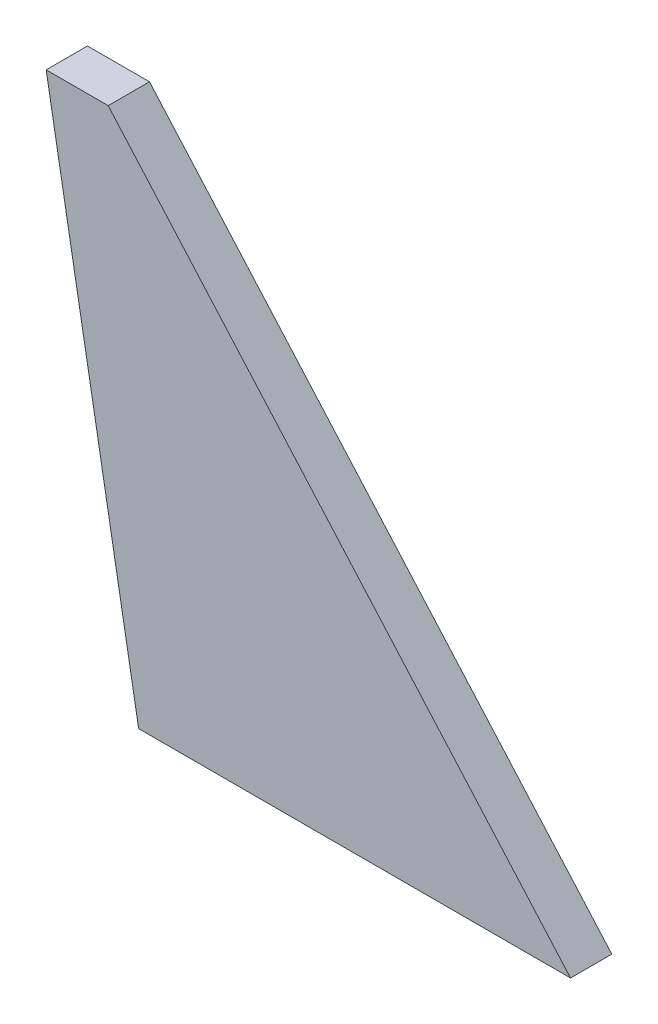
SolidWorks part; units mm, degrees
ref_plane "Front Plane" through (0, 0, 0) normal (0, 0, 1) x (1, 0, 0)
ref_plane "Top Plane" through (0, 0, 0) normal (0, 1, 0) x (1, 0, 0)
ref_plane "Right Plane" through (0, 0, 0) normal (1, 0, 0) x (0, 0, -1)
sketch "Sketch1" plane through (0, 0, 0) normal (0, 0, 1) x (1, 0, 0)
  line L6 (0, 25.4) -> (4.4787, 0)
  line L7 (4.4787, 0) -> (25.4, 0)
  line L9 (0, 25.4) -> (3.0035, 25.4)
  line L11 (3.0035, 25.4) -> (25.4, 0)
  dimension "D3" = 80
extrude "Boss-Extrude2" add sketch "Sketch1" along normal blind 2
